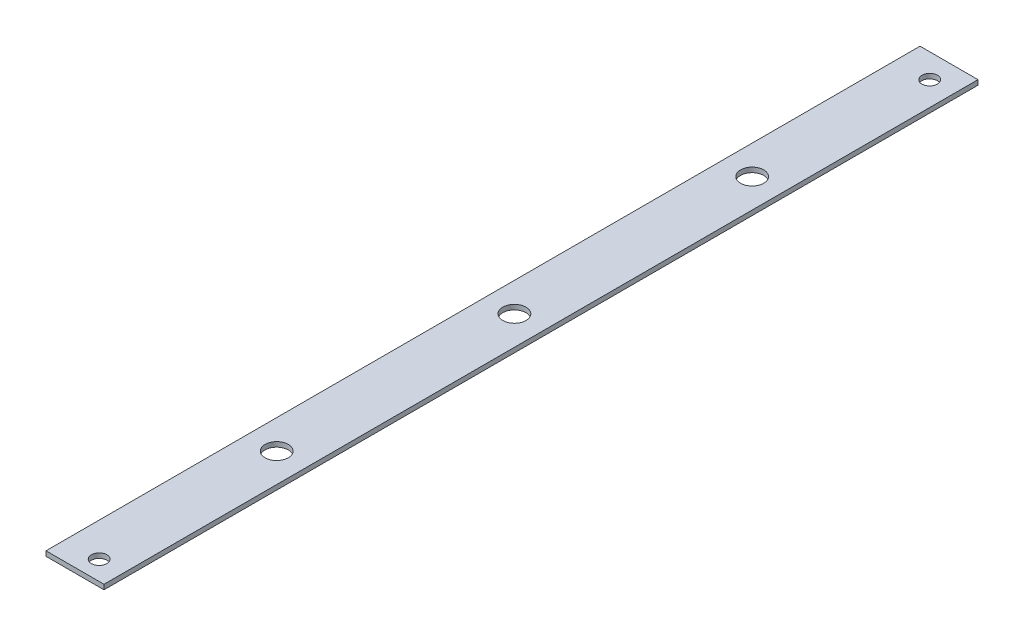
SolidWorks part; units mm, degrees
ref_plane "Front Plane" through (0, 0, 0) normal (0, 0, 1) x (1, 0, 0)
ref_plane "Top Plane" through (0, 0, 0) normal (0, 1, 0) x (1, 0, 0)
ref_plane "Right Plane" through (0, 0, 0) normal (1, 0, 0) x (0, 0, -1)
sketch "Sketch1" plane through (0, 0, 0) normal (0, 0, 1) x (1, 0, 0)
  line L0 (0, 0) -> (0, 2.5)
  line L1 (0, 2.5) -> (2.5, 2.5)
  line L3 (2.5, 2.5) -> (30, 2.5)
  line L4 (30, 2.5) -> (30, 0)
  line L5 (30, 0) -> (0, 0)
  dimension "D2" = 2.5
  dimension "D4" = 30
extrude "Boss-Extrude1" add sketch "Sketch1" along normal mid plane 452.2
sketch "Sketch2" plane through (0, 2.5, 0) normal (0, 1, 0) x (1, 0, 0)
  line L2 (30, -226.1) -> (30, 226.1) construction
  line L3 (0, 226.1) -> (30, 226.1) construction
  line L6 (30, -226.1) -> (0, -226.1) construction
  circle A0 centre (17.5, 213.6) radius 4
  circle A1 centre (17.5, -216.1) radius 4
  circle A2 centre (15, -121.75) radius 6
  circle A3 centre (15, 124.25) radius 6
  circle A4 centre (15, 1.25) radius 6
  point P9 (15, 226.1)
  dimension "D2" = 8
  dimension "D6" = 12
  dimension "D10" = 123
  dimension "D11" = 15
  dimension "D12" = 12
  dimension "D8" = 12
  dimension "D3" = 12.5
  dimension "D4" = 12.5
  dimension "D5" = 10
  dimension "D7" = 15
  dimension "D9" = 15
  dimension "D13" = 123
extrude "Cut-Extrude1" cut sketch "Sketch2" against normal through all
